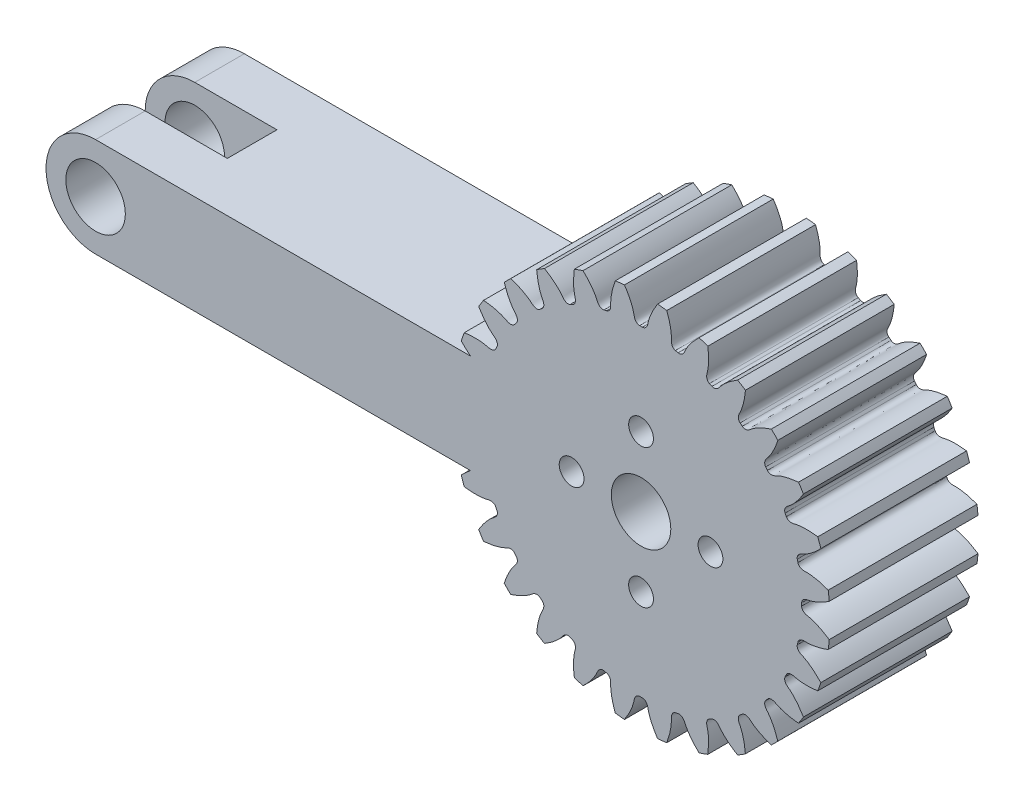
SolidWorks part; units mm, degrees
ref_plane "前视基准面" through (0, 0, 0) normal (0, 0, 1) x (1, 0, 0)
ref_plane "上视基准面" through (0, 0, 0) normal (0, 1, 0) x (1, 0, 0)
ref_plane "右视基准面" through (0, 0, 0) normal (1, 0, 0) x (0, 0, -1)
other "Configuration Table"
sketch "草图1" plane through (0, 0, 0) normal (0, 0, 1) x (1, 0, 0)
  line L4 (-55, -5) -> (-17.1897, -5)
  line L5 (-17.1897, 5) -> (-55, 5)
  circle A0 centre (0, 0) radius 3
  circle A1 centre (-55, 0) radius 3
  arc A104 (-18.1289, -5.8518) -> (-17.8223, -6.7281) centre (0, 0) ccw
  arc A105 (-14.6488, -6.9) -> (-14.528, -7.1508) centre (0, 0) ccw
  arc A106 (-16.3722, -9.7392) -> (-15.8784, -10.5252) centre (0, 0) ccw
  arc A107 (-12.7461, -9.9866) -> (-12.5725, -10.2043) centre (0, 0) ccw
  arc A108 (-13.7946, -13.1382) -> (-13.1382, -13.7946) centre (0, 0) ccw
  arc A109 (-10.2043, -12.5725) -> (-9.9866, -12.7461) centre (0, 0) ccw
  arc A110 (-10.5252, -15.8784) -> (-9.7392, -16.3722) centre (0, 0) ccw
  arc A111 (-7.1508, -14.528) -> (-6.9, -14.6488) centre (0, 0) ccw
  arc A112 (-6.7281, -17.8223) -> (-5.8518, -18.1289) centre (0, 0) ccw
  arc A113 (-3.7388, -15.755) -> (-3.4673, -15.8169) centre (0, 0) ccw
  arc A114 (-2.5935, -18.8726) -> (-1.6711, -18.9766) centre (0, 0) ccw
  arc A115 (-0.1392, -16.1919) -> (0.1392, -16.1919) centre (0, 0) ccw
  arc A116 (1.6711, -18.9766) -> (2.5935, -18.8726) centre (0, 0) ccw
  arc A117 (3.4673, -15.8169) -> (3.7388, -15.755) centre (0, 0) ccw
  arc A118 (5.8518, -18.1289) -> (6.7281, -17.8223) centre (0, 0) ccw
  arc A119 (6.9, -14.6488) -> (7.1508, -14.528) centre (0, 0) ccw
  arc A120 (9.7392, -16.3722) -> (10.5252, -15.8784) centre (0, 0) ccw
  arc A121 (9.9866, -12.7461) -> (10.2043, -12.5725) centre (0, 0) ccw
  arc A122 (13.1382, -13.7946) -> (13.7946, -13.1382) centre (0, 0) ccw
  arc A123 (12.5725, -10.2043) -> (12.7461, -9.9866) centre (0, 0) ccw
  arc A124 (15.8784, -10.5252) -> (16.3722, -9.7392) centre (0, 0) ccw
  arc A125 (14.528, -7.1508) -> (14.6488, -6.9) centre (0, 0) ccw
  arc A126 (17.8223, -6.7281) -> (18.1289, -5.8518) centre (0, 0) ccw
  arc A127 (15.755, -3.7388) -> (15.8169, -3.4673) centre (0, 0) ccw
  arc A128 (18.8726, -2.5935) -> (18.9766, -1.6711) centre (0, 0) ccw
  arc A129 (16.1919, -0.1392) -> (16.1919, 0.1392) centre (0, 0) ccw
  arc A130 (18.9766, 1.6711) -> (18.8726, 2.5935) centre (0, 0) ccw
  arc A131 (15.8169, 3.4673) -> (15.755, 3.7388) centre (0, 0) ccw
  arc A132 (18.1289, 5.8518) -> (17.8223, 6.7281) centre (0, 0) ccw
  arc A133 (14.6488, 6.9) -> (14.528, 7.1508) centre (0, 0) ccw
  arc A134 (16.3722, 9.7392) -> (15.8784, 10.5252) centre (0, 0) ccw
  arc A135 (12.7461, 9.9866) -> (12.5725, 10.2043) centre (0, 0) ccw
  arc A136 (13.7946, 13.1382) -> (13.1382, 13.7946) centre (0, 0) ccw
  arc A137 (10.2043, 12.5725) -> (9.9866, 12.7461) centre (0, 0) ccw
  arc A138 (10.5252, 15.8784) -> (9.7392, 16.3722) centre (0, 0) ccw
  arc A139 (7.1508, 14.528) -> (6.9, 14.6488) centre (0, 0) ccw
  arc A140 (6.7281, 17.8223) -> (5.8518, 18.1289) centre (0, 0) ccw
  arc A141 (3.7388, 15.755) -> (3.4673, 15.8169) centre (0, 0) ccw
  arc A142 (2.5935, 18.8726) -> (1.6711, 18.9766) centre (0, 0) ccw
  arc A143 (0.1392, 16.1919) -> (-0.1392, 16.1919) centre (0, 0) ccw
  arc A144 (-1.6711, 18.9766) -> (-2.5935, 18.8726) centre (0, 0) ccw
  arc A145 (-3.4673, 15.8169) -> (-3.7388, 15.755) centre (0, 0) ccw
  arc A146 (-5.8518, 18.1289) -> (-6.7281, 17.8223) centre (0, 0) ccw
  arc A147 (-6.9, 14.6488) -> (-7.1508, 14.528) centre (0, 0) ccw
  arc A148 (-9.7392, 16.3722) -> (-10.5252, 15.8784) centre (0, 0) ccw
  arc A149 (-9.9866, 12.7461) -> (-10.2043, 12.5725) centre (0, 0) ccw
  arc A150 (-13.1382, 13.7946) -> (-13.7946, 13.1382) centre (0, 0) ccw
  arc A151 (-12.5725, 10.2043) -> (-12.7461, 9.9866) centre (0, 0) ccw
  arc A152 (-15.8784, 10.5252) -> (-16.3722, 9.7392) centre (0, 0) ccw
  arc A153 (-14.528, 7.1508) -> (-14.6488, 6.9) centre (0, 0) ccw
  arc A154 (-17.8223, 6.7281) -> (-18.1289, 5.8518) centre (0, 0) ccw
  arc A155 (-55, 5) -> (-55, -5) centre (-55, 0) ccw
  spline S104 degree 3 poles (-17.1897, -5) (-17.2348, -5.0343) (-17.3497, -5.1242) (-17.5362, -5.2798) (-17.8086, -5.525) (-18.005, -5.7208) (-18.1289, -5.8518) knots 0.59534 0.59534 0.59534 0.59534 0.645252 0.723706 0.808982 0.967655 0.967655 0.967655 0.967655
  spline S105 degree 3 poles (-17.8223, -6.7281) (-17.6438, -6.7532) (-17.3681, -6.7839) (-17.0023, -6.8057) (-16.7348, -6.8117) (-16.4906, -6.808) (-16.2698, -6.7965) (-16.0729, -6.7788) (-15.8998, -6.7568) (-15.7506, -6.7322) (-15.6252, -6.7066) (-15.5335, -6.6846) (-15.4713, -6.6672) (-15.4305, -6.6561) (-15.3936, -6.6472) (-15.3338, -6.6343) (-15.2507, -6.6212) (-15.1426, -6.6153) (-15.0302, -6.6239) (-14.9083, -6.6553) (-14.7624, -6.7338) (-14.6816, -6.8327) (-14.6488, -6.9) knots 0.032345 0.032345 0.032345 0.032345 0.191018 0.276294 0.354748 0.42638 0.49119 0.549178 0.600343 0.644687 0.682208 0.712908 0.727669 0.739016 0.750139 0.761058 0.792861 0.824038 0.856152 0.891705 0.934026 1 1 1 1
  spline S106 degree 3 poles (-14.528, -7.1508) (-14.4959, -7.2184) (-14.4689, -7.3433) (-14.4985, -7.5063) (-14.5499, -7.6211) (-14.6133, -7.7144) (-14.6854, -7.7952) (-14.7474, -7.852) (-14.7948, -7.8908) (-14.8247, -7.9141) (-14.8589, -7.939) (-14.9112, -7.9768) (-14.9856, -8.0348) (-15.0838, -8.1169) (-15.1961, -8.2182) (-15.3212, -8.3398) (-15.4578, -8.4827) (-15.6044, -8.6481) (-15.7595, -8.8368) (-15.9217, -9.0496) (-16.1327, -9.3492) (-16.2806, -9.5839) (-16.3722, -9.7392) knots 0 0 0 0 0.065974 0.108295 0.143848 0.175962 0.207139 0.238942 0.249861 0.260984 0.272331 0.287092 0.317792 0.355313 0.399657 0.450822 0.50881 0.57362 0.645252 0.723706 0.808982 0.967655 0.967655 0.967655 0.967655
  spline S107 degree 3 poles (-15.8784, -10.5252) (-15.6987, -10.51) (-15.4231, -10.4786) (-15.0616, -10.4184) (-14.7995, -10.3647) (-14.5622, -10.3068) (-14.3496, -10.2465) (-14.1615, -10.1854) (-13.9976, -10.1255) (-13.8577, -10.0683) (-13.7411, -10.0154) (-13.6566, -9.9735) (-13.5998, -9.9428) (-13.5625, -9.9228) (-13.5285, -9.9059) (-13.4731, -9.8801) (-13.395, -9.8488) (-13.2909, -9.819) (-13.1794, -9.8023) (-13.0536, -9.8058) (-12.8939, -9.8499) (-12.7931, -9.9284) (-12.7461, -9.9866) knots 0.032345 0.032345 0.032345 0.032345 0.191018 0.276294 0.354748 0.42638 0.49119 0.549178 0.600343 0.644687 0.682208 0.712908 0.727669 0.739016 0.750139 0.761058 0.792861 0.824038 0.856152 0.891705 0.934026 1 1 1 1
  spline S108 degree 3 poles (-12.5725, -10.2043) (-12.5262, -10.2631) (-12.4721, -10.3788) (-12.4647, -10.5443) (-12.4893, -10.6677) (-12.5303, -10.7727) (-12.5826, -10.8676) (-12.6304, -10.9367) (-12.668, -10.9851) (-12.692, -11.0145) (-12.7197, -11.0464) (-12.7623, -11.0949) (-12.822, -11.168) (-12.8994, -11.2698) (-12.9864, -11.3936) (-13.0813, -11.5399) (-13.1826, -11.7097) (-13.2888, -11.9036) (-13.3981, -12.1221) (-13.5087, -12.3656) (-13.6478, -12.7047) (-13.7398, -12.9664) (-13.7946, -13.1382) knots 0 0 0 0 0.065974 0.108295 0.143848 0.175962 0.207139 0.238942 0.249861 0.260984 0.272331 0.287092 0.317792 0.355313 0.399657 0.450822 0.50881 0.57362 0.645252 0.723706 0.808982 0.967655 0.967655 0.967655 0.967655
  spline S109 degree 3 poles (-13.1382, -13.7946) (-12.9664, -13.7398) (-12.7047, -13.6478) (-12.3656, -13.5087) (-12.1221, -13.3981) (-11.9036, -13.2888) (-11.7097, -13.1826) (-11.5399, -13.0813) (-11.3936, -12.9864) (-11.2698, -12.8994) (-11.168, -12.822) (-11.0949, -12.7623) (-11.0464, -12.7197) (-11.0145, -12.692) (-10.9851, -12.668) (-10.9367, -12.6304) (-10.8676, -12.5826) (-10.7727, -12.5303) (-10.6677, -12.4893) (-10.5443, -12.4647) (-10.3788, -12.4721) (-10.2631, -12.5262) (-10.2043, -12.5725) knots 0.032345 0.032345 0.032345 0.032345 0.191018 0.276294 0.354748 0.42638 0.49119 0.549178 0.600343 0.644687 0.682208 0.712908 0.727669 0.739016 0.750139 0.761058 0.792861 0.824038 0.856152 0.891705 0.934026 1 1 1 1
  spline S110 degree 3 poles (-9.9866, -12.7461) (-9.9284, -12.7931) (-9.8499, -12.8939) (-9.8058, -13.0536) (-9.8023, -13.1794) (-9.819, -13.2909) (-9.8488, -13.395) (-9.8801, -13.4731) (-9.9059, -13.5285) (-9.9228, -13.5625) (-9.9428, -13.5998) (-9.9735, -13.6566) (-10.0154, -13.7411) (-10.0683, -13.8577) (-10.1255, -13.9976) (-10.1854, -14.1615) (-10.2465, -14.3496) (-10.3068, -14.5622) (-10.3647, -14.7995) (-10.4184, -15.0616) (-10.4786, -15.4231) (-10.51, -15.6987) (-10.5252, -15.8784) knots 0 0 0 0 0.065974 0.108295 0.143848 0.175962 0.207139 0.238942 0.249861 0.260984 0.272331 0.287092 0.317792 0.355313 0.399657 0.450822 0.50881 0.57362 0.645252 0.723706 0.808982 0.967655 0.967655 0.967655 0.967655
  spline S111 degree 3 poles (-9.7392, -16.3722) (-9.5839, -16.2806) (-9.3492, -16.1327) (-9.0496, -15.9217) (-8.8368, -15.7595) (-8.6481, -15.6044) (-8.4827, -15.4578) (-8.3398, -15.3212) (-8.2182, -15.1961) (-8.1169, -15.0838) (-8.0348, -14.9856) (-7.9768, -14.9112) (-7.939, -14.8589) (-7.9141, -14.8247) (-7.8908, -14.7948) (-7.852, -14.7474) (-7.7952, -14.6854) (-7.7144, -14.6133) (-7.6211, -14.5499) (-7.5063, -14.4985) (-7.3433, -14.4689) (-7.2184, -14.4959) (-7.1508, -14.528) knots 0.032345 0.032345 0.032345 0.032345 0.191018 0.276294 0.354748 0.42638 0.49119 0.549178 0.600343 0.644687 0.682208 0.712908 0.727669 0.739016 0.750139 0.761058 0.792861 0.824038 0.856152 0.891705 0.934026 1 1 1 1
  spline S112 degree 3 poles (-6.9, -14.6488) (-6.8327, -14.6816) (-6.7338, -14.7624) (-6.6553, -14.9083) (-6.6239, -15.0302) (-6.6153, -15.1426) (-6.6212, -15.2507) (-6.6343, -15.3338) (-6.6472, -15.3936) (-6.6561, -15.4305) (-6.6672, -15.4713) (-6.6846, -15.5335) (-6.7066, -15.6252) (-6.7322, -15.7506) (-6.7568, -15.8998) (-6.7788, -16.0729) (-6.7965, -16.2698) (-6.808, -16.4906) (-6.8117, -16.7348) (-6.8057, -17.0023) (-6.7839, -17.3681) (-6.7532, -17.6438) (-6.7281, -17.8223) knots 0 0 0 0 0.065974 0.108295 0.143848 0.175962 0.207139 0.238942 0.249861 0.260984 0.272331 0.287092 0.317792 0.355313 0.399657 0.450822 0.50881 0.57362 0.645252 0.723706 0.808982 0.967655 0.967655 0.967655 0.967655
  spline S113 degree 3 poles (-5.8518, -18.1289) (-5.7208, -18.005) (-5.525, -17.8086) (-5.2798, -17.5362) (-5.1084, -17.3308) (-4.959, -17.1376) (-4.8304, -16.9578) (-4.7214, -16.7928) (-4.6307, -16.6438) (-4.5569, -16.5118) (-4.4987, -16.3978) (-4.4588, -16.3124) (-4.4336, -16.2529) (-4.4168, -16.2141) (-4.4008, -16.1797) (-4.3735, -16.1249) (-4.332, -16.0518) (-4.2692, -15.9635) (-4.1924, -15.881) (-4.0919, -15.8053) (-3.9395, -15.7401) (-3.8118, -15.7387) (-3.7388, -15.755) knots 0.032345 0.032345 0.032345 0.032345 0.191018 0.276294 0.354748 0.42638 0.49119 0.549178 0.600343 0.644687 0.682208 0.712908 0.727669 0.739016 0.750139 0.761058 0.792861 0.824038 0.856152 0.891705 0.934026 1 1 1 1
  spline S114 degree 3 poles (-3.4673, -15.8169) (-3.3945, -15.8339) (-3.28, -15.8907) (-3.171, -16.0155) (-3.1133, -16.1273) (-3.0799, -16.235) (-3.0616, -16.3417) (-3.0559, -16.4256) (-3.0551, -16.4868) (-3.0556, -16.5248) (-3.0574, -16.567) (-3.0604, -16.6315) (-3.0615, -16.7259) (-3.0586, -16.8538) (-3.0494, -17.0047) (-3.0323, -17.1783) (-3.0057, -17.3743) (-2.9678, -17.592) (-2.917, -17.831) (-2.8517, -18.0904) (-2.749, -18.4422) (-2.6578, -18.7041) (-2.5935, -18.8726) knots 0 0 0 0 0.065974 0.108295 0.143848 0.175962 0.207139 0.238942 0.249861 0.260984 0.272331 0.287092 0.317792 0.355313 0.399657 0.450822 0.50881 0.57362 0.645252 0.723706 0.808982 0.967655 0.967655 0.967655 0.967655
  spline S115 degree 3 poles (-1.6711, -18.9766) (-1.5709, -18.8266) (-1.4237, -18.5915) (-1.2453, -18.2714) (-1.1239, -18.033) (-1.0212, -17.8114) (-0.9358, -17.6075) (-0.8662, -17.4224) (-0.811, -17.2569) (-0.7684, -17.1118) (-0.7371, -16.9878) (-0.7172, -16.8956) (-0.7058, -16.832) (-0.6981, -16.7904) (-0.6901, -16.7533) (-0.6758, -16.6938) (-0.6515, -16.6133) (-0.6099, -16.5133) (-0.5534, -16.4157) (-0.4723, -16.3196) (-0.3383, -16.2221) (-0.214, -16.1923) (-0.1392, -16.1919) knots 0.032345 0.032345 0.032345 0.032345 0.191018 0.276294 0.354748 0.42638 0.49119 0.549178 0.600343 0.644687 0.682208 0.712908 0.727669 0.739016 0.750139 0.761058 0.792861 0.824038 0.856152 0.891705 0.934026 1 1 1 1
  spline S116 degree 3 poles (0.1392, -16.1919) (0.214, -16.1923) (0.3383, -16.2221) (0.4723, -16.3196) (0.5534, -16.4157) (0.6099, -16.5133) (0.6515, -16.6133) (0.6758, -16.6938) (0.6901, -16.7533) (0.6981, -16.7904) (0.7058, -16.832) (0.7172, -16.8956) (0.7371, -16.9878) (0.7684, -17.1118) (0.811, -17.2569) (0.8662, -17.4224) (0.9358, -17.6075) (1.0212, -17.8114) (1.1239, -18.033) (1.2453, -18.2714) (1.4237, -18.5915) (1.5709, -18.8266) (1.6711, -18.9766) knots 0 0 0 0 0.065974 0.108295 0.143848 0.175962 0.207139 0.238942 0.249861 0.260984 0.272331 0.287092 0.317792 0.355313 0.399657 0.450822 0.50881 0.57362 0.645252 0.723706 0.808982 0.967655 0.967655 0.967655 0.967655
  spline S117 degree 3 poles (2.5935, -18.8726) (2.6578, -18.7041) (2.749, -18.4422) (2.8517, -18.0904) (2.917, -17.831) (2.9678, -17.592) (3.0057, -17.3743) (3.0323, -17.1783) (3.0494, -17.0047) (3.0586, -16.8538) (3.0615, -16.7259) (3.0604, -16.6315) (3.0574, -16.567) (3.0556, -16.5248) (3.0551, -16.4868) (3.0559, -16.4256) (3.0616, -16.3417) (3.0799, -16.235) (3.1133, -16.1273) (3.171, -16.0155) (3.28, -15.8907) (3.3945, -15.8339) (3.4673, -15.8169) knots 0.032345 0.032345 0.032345 0.032345 0.191018 0.276294 0.354748 0.42638 0.49119 0.549178 0.600343 0.644687 0.682208 0.712908 0.727669 0.739016 0.750139 0.761058 0.792861 0.824038 0.856152 0.891705 0.934026 1 1 1 1
  spline S118 degree 3 poles (3.7388, -15.755) (3.8118, -15.7387) (3.9395, -15.7401) (4.0919, -15.8053) (4.1924, -15.881) (4.2692, -15.9635) (4.332, -16.0518) (4.3735, -16.1249) (4.4008, -16.1797) (4.4168, -16.2141) (4.4336, -16.2529) (4.4588, -16.3124) (4.4987, -16.3978) (4.5569, -16.5118) (4.6307, -16.6438) (4.7214, -16.7928) (4.8304, -16.9578) (4.959, -17.1376) (5.1084, -17.3308) (5.2798, -17.5362) (5.525, -17.8086) (5.7208, -18.005) (5.8518, -18.1289) knots 0 0 0 0 0.065974 0.108295 0.143848 0.175962 0.207139 0.238942 0.249861 0.260984 0.272331 0.287092 0.317792 0.355313 0.399657 0.450822 0.50881 0.57362 0.645252 0.723706 0.808982 0.967655 0.967655 0.967655 0.967655
  spline S119 degree 3 poles (6.7281, -17.8223) (6.7532, -17.6438) (6.7839, -17.3681) (6.8057, -17.0023) (6.8117, -16.7348) (6.808, -16.4906) (6.7965, -16.2698) (6.7788, -16.0729) (6.7568, -15.8998) (6.7322, -15.7506) (6.7066, -15.6252) (6.6846, -15.5335) (6.6672, -15.4713) (6.6561, -15.4305) (6.6472, -15.3936) (6.6343, -15.3338) (6.6212, -15.2507) (6.6153, -15.1426) (6.6239, -15.0302) (6.6553, -14.9083) (6.7338, -14.7624) (6.8327, -14.6816) (6.9, -14.6488) knots 0.032345 0.032345 0.032345 0.032345 0.191018 0.276294 0.354748 0.42638 0.49119 0.549178 0.600343 0.644687 0.682208 0.712908 0.727669 0.739016 0.750139 0.761058 0.792861 0.824038 0.856152 0.891705 0.934026 1 1 1 1
  spline S120 degree 3 poles (7.1508, -14.528) (7.2184, -14.4959) (7.3433, -14.4689) (7.5063, -14.4985) (7.6211, -14.5499) (7.7144, -14.6133) (7.7952, -14.6854) (7.852, -14.7474) (7.8908, -14.7948) (7.9141, -14.8247) (7.939, -14.8589) (7.9768, -14.9112) (8.0348, -14.9856) (8.1169, -15.0838) (8.2182, -15.1961) (8.3398, -15.3212) (8.4827, -15.4578) (8.6481, -15.6044) (8.8368, -15.7595) (9.0496, -15.9217) (9.3492, -16.1327) (9.5839, -16.2806) (9.7392, -16.3722) knots 0 0 0 0 0.065974 0.108295 0.143848 0.175962 0.207139 0.238942 0.249861 0.260984 0.272331 0.287092 0.317792 0.355313 0.399657 0.450822 0.50881 0.57362 0.645252 0.723706 0.808982 0.967655 0.967655 0.967655 0.967655
  spline S121 degree 3 poles (10.5252, -15.8784) (10.51, -15.6987) (10.4786, -15.4231) (10.4184, -15.0616) (10.3647, -14.7995) (10.3068, -14.5622) (10.2465, -14.3496) (10.1854, -14.1615) (10.1255, -13.9976) (10.0683, -13.8577) (10.0154, -13.7411) (9.9735, -13.6566) (9.9428, -13.5998) (9.9228, -13.5625) (9.9059, -13.5285) (9.8801, -13.4731) (9.8488, -13.395) (9.819, -13.2909) (9.8023, -13.1794) (9.8058, -13.0536) (9.8499, -12.8939) (9.9284, -12.7931) (9.9866, -12.7461) knots 0.032345 0.032345 0.032345 0.032345 0.191018 0.276294 0.354748 0.42638 0.49119 0.549178 0.600343 0.644687 0.682208 0.712908 0.727669 0.739016 0.750139 0.761058 0.792861 0.824038 0.856152 0.891705 0.934026 1 1 1 1
  spline S122 degree 3 poles (10.2043, -12.5725) (10.2631, -12.5262) (10.3788, -12.4721) (10.5443, -12.4647) (10.6677, -12.4893) (10.7727, -12.5303) (10.8676, -12.5826) (10.9367, -12.6304) (10.9851, -12.668) (11.0145, -12.692) (11.0464, -12.7197) (11.0949, -12.7623) (11.168, -12.822) (11.2698, -12.8994) (11.3936, -12.9864) (11.5399, -13.0813) (11.7097, -13.1826) (11.9036, -13.2888) (12.1221, -13.3981) (12.3656, -13.5087) (12.7047, -13.6478) (12.9664, -13.7398) (13.1382, -13.7946) knots 0 0 0 0 0.065974 0.108295 0.143848 0.175962 0.207139 0.238942 0.249861 0.260984 0.272331 0.287092 0.317792 0.355313 0.399657 0.450822 0.50881 0.57362 0.645252 0.723706 0.808982 0.967655 0.967655 0.967655 0.967655
  spline S123 degree 3 poles (13.7946, -13.1382) (13.7398, -12.9664) (13.6478, -12.7047) (13.5087, -12.3656) (13.3981, -12.1221) (13.2888, -11.9036) (13.1826, -11.7097) (13.0813, -11.5399) (12.9864, -11.3936) (12.8994, -11.2698) (12.822, -11.168) (12.7623, -11.0949) (12.7197, -11.0464) (12.692, -11.0145) (12.668, -10.9851) (12.6304, -10.9367) (12.5826, -10.8676) (12.5303, -10.7727) (12.4893, -10.6677) (12.4647, -10.5443) (12.4721, -10.3788) (12.5262, -10.2631) (12.5725, -10.2043) knots 0.032345 0.032345 0.032345 0.032345 0.191018 0.276294 0.354748 0.42638 0.49119 0.549178 0.600343 0.644687 0.682208 0.712908 0.727669 0.739016 0.750139 0.761058 0.792861 0.824038 0.856152 0.891705 0.934026 1 1 1 1
  spline S124 degree 3 poles (12.7461, -9.9866) (12.7931, -9.9284) (12.8939, -9.8499) (13.0536, -9.8058) (13.1794, -9.8023) (13.2909, -9.819) (13.395, -9.8488) (13.4731, -9.8801) (13.5285, -9.9059) (13.5625, -9.9228) (13.5998, -9.9428) (13.6566, -9.9735) (13.7411, -10.0154) (13.8577, -10.0683) (13.9976, -10.1255) (14.1615, -10.1854) (14.3496, -10.2465) (14.5622, -10.3068) (14.7995, -10.3647) (15.0616, -10.4184) (15.4231, -10.4786) (15.6987, -10.51) (15.8784, -10.5252) knots 0 0 0 0 0.065974 0.108295 0.143848 0.175962 0.207139 0.238942 0.249861 0.260984 0.272331 0.287092 0.317792 0.355313 0.399657 0.450822 0.50881 0.57362 0.645252 0.723706 0.808982 0.967655 0.967655 0.967655 0.967655
  spline S125 degree 3 poles (16.3722, -9.7392) (16.2806, -9.5839) (16.1327, -9.3492) (15.9217, -9.0496) (15.7595, -8.8368) (15.6044, -8.6481) (15.4578, -8.4827) (15.3212, -8.3398) (15.1961, -8.2182) (15.0838, -8.1169) (14.9856, -8.0348) (14.9112, -7.9768) (14.8589, -7.939) (14.8247, -7.9141) (14.7948, -7.8908) (14.7474, -7.852) (14.6854, -7.7952) (14.6133, -7.7144) (14.5499, -7.6211) (14.4985, -7.5063) (14.4689, -7.3433) (14.4959, -7.2184) (14.528, -7.1508) knots 0.032345 0.032345 0.032345 0.032345 0.191018 0.276294 0.354748 0.42638 0.49119 0.549178 0.600343 0.644687 0.682208 0.712908 0.727669 0.739016 0.750139 0.761058 0.792861 0.824038 0.856152 0.891705 0.934026 1 1 1 1
  spline S126 degree 3 poles (14.6488, -6.9) (14.6816, -6.8327) (14.7624, -6.7338) (14.9083, -6.6553) (15.0302, -6.6239) (15.1426, -6.6153) (15.2507, -6.6212) (15.3338, -6.6343) (15.3936, -6.6472) (15.4305, -6.6561) (15.4713, -6.6672) (15.5335, -6.6846) (15.6252, -6.7066) (15.7506, -6.7322) (15.8998, -6.7568) (16.0729, -6.7788) (16.2698, -6.7965) (16.4906, -6.808) (16.7348, -6.8117) (17.0023, -6.8057) (17.3681, -6.7839) (17.6438, -6.7532) (17.8223, -6.7281) knots 0 0 0 0 0.065974 0.108295 0.143848 0.175962 0.207139 0.238942 0.249861 0.260984 0.272331 0.287092 0.317792 0.355313 0.399657 0.450822 0.50881 0.57362 0.645252 0.723706 0.808982 0.967655 0.967655 0.967655 0.967655
  spline S127 degree 3 poles (18.1289, -5.8518) (18.005, -5.7208) (17.8086, -5.525) (17.5362, -5.2798) (17.3308, -5.1084) (17.1376, -4.959) (16.9578, -4.8304) (16.7928, -4.7214) (16.6438, -4.6307) (16.5118, -4.5569) (16.3978, -4.4987) (16.3124, -4.4588) (16.2529, -4.4336) (16.2141, -4.4168) (16.1797, -4.4008) (16.1249, -4.3735) (16.0518, -4.332) (15.9635, -4.2692) (15.881, -4.1924) (15.8053, -4.0919) (15.7401, -3.9395) (15.7387, -3.8118) (15.755, -3.7388) knots 0.032345 0.032345 0.032345 0.032345 0.191018 0.276294 0.354748 0.42638 0.49119 0.549178 0.600343 0.644687 0.682208 0.712908 0.727669 0.739016 0.750139 0.761058 0.792861 0.824038 0.856152 0.891705 0.934026 1 1 1 1
  spline S128 degree 3 poles (15.8169, -3.4673) (15.8339, -3.3945) (15.8907, -3.28) (16.0155, -3.171) (16.1273, -3.1133) (16.235, -3.0799) (16.3417, -3.0616) (16.4256, -3.0559) (16.4868, -3.0551) (16.5248, -3.0556) (16.567, -3.0574) (16.6315, -3.0604) (16.7259, -3.0615) (16.8538, -3.0586) (17.0047, -3.0494) (17.1783, -3.0323) (17.3743, -3.0057) (17.592, -2.9678) (17.831, -2.917) (18.0904, -2.8517) (18.4422, -2.749) (18.7041, -2.6578) (18.8726, -2.5935) knots 0 0 0 0 0.065974 0.108295 0.143848 0.175962 0.207139 0.238942 0.249861 0.260984 0.272331 0.287092 0.317792 0.355313 0.399657 0.450822 0.50881 0.57362 0.645252 0.723706 0.808982 0.967655 0.967655 0.967655 0.967655
  spline S129 degree 3 poles (18.9766, -1.6711) (18.8266, -1.5709) (18.5915, -1.4237) (18.2714, -1.2453) (18.033, -1.1239) (17.8114, -1.0212) (17.6075, -0.9358) (17.4224, -0.8662) (17.2569, -0.811) (17.1118, -0.7684) (16.9878, -0.7371) (16.8956, -0.7172) (16.832, -0.7058) (16.7904, -0.6981) (16.7533, -0.6901) (16.6938, -0.6758) (16.6133, -0.6515) (16.5133, -0.6099) (16.4157, -0.5534) (16.3196, -0.4723) (16.2221, -0.3383) (16.1923, -0.214) (16.1919, -0.1392) knots 0.032345 0.032345 0.032345 0.032345 0.191018 0.276294 0.354748 0.42638 0.49119 0.549178 0.600343 0.644687 0.682208 0.712908 0.727669 0.739016 0.750139 0.761058 0.792861 0.824038 0.856152 0.891705 0.934026 1 1 1 1
  spline S130 degree 3 poles (16.1919, 0.1392) (16.1923, 0.214) (16.2221, 0.3383) (16.3196, 0.4723) (16.4157, 0.5534) (16.5133, 0.6099) (16.6133, 0.6515) (16.6938, 0.6758) (16.7533, 0.6901) (16.7904, 0.6981) (16.832, 0.7058) (16.8956, 0.7172) (16.9878, 0.7371) (17.1118, 0.7684) (17.2569, 0.811) (17.4224, 0.8662) (17.6075, 0.9358) (17.8114, 1.0212) (18.033, 1.1239) (18.2714, 1.2453) (18.5915, 1.4237) (18.8266, 1.5709) (18.9766, 1.6711) knots 0 0 0 0 0.065974 0.108295 0.143848 0.175962 0.207139 0.238942 0.249861 0.260984 0.272331 0.287092 0.317792 0.355313 0.399657 0.450822 0.50881 0.57362 0.645252 0.723706 0.808982 0.967655 0.967655 0.967655 0.967655
  spline S131 degree 3 poles (18.8726, 2.5935) (18.7041, 2.6578) (18.4422, 2.749) (18.0904, 2.8517) (17.831, 2.917) (17.592, 2.9678) (17.3743, 3.0057) (17.1783, 3.0323) (17.0047, 3.0494) (16.8538, 3.0586) (16.7259, 3.0615) (16.6315, 3.0604) (16.567, 3.0574) (16.5248, 3.0556) (16.4868, 3.0551) (16.4256, 3.0559) (16.3417, 3.0616) (16.235, 3.0799) (16.1273, 3.1133) (16.0155, 3.171) (15.8907, 3.28) (15.8339, 3.3945) (15.8169, 3.4673) knots 0.032345 0.032345 0.032345 0.032345 0.191018 0.276294 0.354748 0.42638 0.49119 0.549178 0.600343 0.644687 0.682208 0.712908 0.727669 0.739016 0.750139 0.761058 0.792861 0.824038 0.856152 0.891705 0.934026 1 1 1 1
  spline S132 degree 3 poles (15.755, 3.7388) (15.7387, 3.8118) (15.7401, 3.9395) (15.8053, 4.0919) (15.881, 4.1924) (15.9635, 4.2692) (16.0518, 4.332) (16.1249, 4.3735) (16.1797, 4.4008) (16.2141, 4.4168) (16.2529, 4.4336) (16.3124, 4.4588) (16.3978, 4.4987) (16.5118, 4.5569) (16.6438, 4.6307) (16.7928, 4.7214) (16.9578, 4.8304) (17.1376, 4.959) (17.3308, 5.1084) (17.5362, 5.2798) (17.8086, 5.525) (18.005, 5.7208) (18.1289, 5.8518) knots 0 0 0 0 0.065974 0.108295 0.143848 0.175962 0.207139 0.238942 0.249861 0.260984 0.272331 0.287092 0.317792 0.355313 0.399657 0.450822 0.50881 0.57362 0.645252 0.723706 0.808982 0.967655 0.967655 0.967655 0.967655
  spline S133 degree 3 poles (17.8223, 6.7281) (17.6438, 6.7532) (17.3681, 6.7839) (17.0023, 6.8057) (16.7348, 6.8117) (16.4906, 6.808) (16.2698, 6.7965) (16.0729, 6.7788) (15.8998, 6.7568) (15.7506, 6.7322) (15.6252, 6.7066) (15.5335, 6.6846) (15.4713, 6.6672) (15.4305, 6.6561) (15.3936, 6.6472) (15.3338, 6.6343) (15.2507, 6.6212) (15.1426, 6.6153) (15.0302, 6.6239) (14.9083, 6.6553) (14.7624, 6.7338) (14.6816, 6.8327) (14.6488, 6.9) knots 0.032345 0.032345 0.032345 0.032345 0.191018 0.276294 0.354748 0.42638 0.49119 0.549178 0.600343 0.644687 0.682208 0.712908 0.727669 0.739016 0.750139 0.761058 0.792861 0.824038 0.856152 0.891705 0.934026 1 1 1 1
  spline S134 degree 3 poles (14.528, 7.1508) (14.4959, 7.2184) (14.4689, 7.3433) (14.4985, 7.5063) (14.5499, 7.6211) (14.6133, 7.7144) (14.6854, 7.7952) (14.7474, 7.852) (14.7948, 7.8908) (14.8247, 7.9141) (14.8589, 7.939) (14.9112, 7.9768) (14.9856, 8.0348) (15.0838, 8.1169) (15.1961, 8.2182) (15.3212, 8.3398) (15.4578, 8.4827) (15.6044, 8.6481) (15.7595, 8.8368) (15.9217, 9.0496) (16.1327, 9.3492) (16.2806, 9.5839) (16.3722, 9.7392) knots 0 0 0 0 0.065974 0.108295 0.143848 0.175962 0.207139 0.238942 0.249861 0.260984 0.272331 0.287092 0.317792 0.355313 0.399657 0.450822 0.50881 0.57362 0.645252 0.723706 0.808982 0.967655 0.967655 0.967655 0.967655
  spline S135 degree 3 poles (15.8784, 10.5252) (15.6987, 10.51) (15.4231, 10.4786) (15.0616, 10.4184) (14.7995, 10.3647) (14.5622, 10.3068) (14.3496, 10.2465) (14.1615, 10.1854) (13.9976, 10.1255) (13.8577, 10.0683) (13.7411, 10.0154) (13.6566, 9.9735) (13.5998, 9.9428) (13.5625, 9.9228) (13.5285, 9.9059) (13.4731, 9.8801) (13.395, 9.8488) (13.2909, 9.819) (13.1794, 9.8023) (13.0536, 9.8058) (12.8939, 9.8499) (12.7931, 9.9284) (12.7461, 9.9866) knots 0.032345 0.032345 0.032345 0.032345 0.191018 0.276294 0.354748 0.42638 0.49119 0.549178 0.600343 0.644687 0.682208 0.712908 0.727669 0.739016 0.750139 0.761058 0.792861 0.824038 0.856152 0.891705 0.934026 1 1 1 1
  spline S136 degree 3 poles (12.5725, 10.2043) (12.5262, 10.2631) (12.4721, 10.3788) (12.4647, 10.5443) (12.4893, 10.6677) (12.5303, 10.7727) (12.5826, 10.8676) (12.6304, 10.9367) (12.668, 10.9851) (12.692, 11.0145) (12.7197, 11.0464) (12.7623, 11.0949) (12.822, 11.168) (12.8994, 11.2698) (12.9864, 11.3936) (13.0813, 11.5399) (13.1826, 11.7097) (13.2888, 11.9036) (13.3981, 12.1221) (13.5087, 12.3656) (13.6478, 12.7047) (13.7398, 12.9664) (13.7946, 13.1382) knots 0 0 0 0 0.065974 0.108295 0.143848 0.175962 0.207139 0.238942 0.249861 0.260984 0.272331 0.287092 0.317792 0.355313 0.399657 0.450822 0.50881 0.57362 0.645252 0.723706 0.808982 0.967655 0.967655 0.967655 0.967655
  spline S137 degree 3 poles (13.1382, 13.7946) (12.9664, 13.7398) (12.7047, 13.6478) (12.3656, 13.5087) (12.1221, 13.3981) (11.9036, 13.2888) (11.7097, 13.1826) (11.5399, 13.0813) (11.3936, 12.9864) (11.2698, 12.8994) (11.168, 12.822) (11.0949, 12.7623) (11.0464, 12.7197) (11.0145, 12.692) (10.9851, 12.668) (10.9367, 12.6304) (10.8676, 12.5826) (10.7727, 12.5303) (10.6677, 12.4893) (10.5443, 12.4647) (10.3788, 12.4721) (10.2631, 12.5262) (10.2043, 12.5725) knots 0.032345 0.032345 0.032345 0.032345 0.191018 0.276294 0.354748 0.42638 0.49119 0.549178 0.600343 0.644687 0.682208 0.712908 0.727669 0.739016 0.750139 0.761058 0.792861 0.824038 0.856152 0.891705 0.934026 1 1 1 1
  spline S138 degree 3 poles (9.9866, 12.7461) (9.9284, 12.7931) (9.8499, 12.8939) (9.8058, 13.0536) (9.8023, 13.1794) (9.819, 13.2909) (9.8488, 13.395) (9.8801, 13.4731) (9.9059, 13.5285) (9.9228, 13.5625) (9.9428, 13.5998) (9.9735, 13.6566) (10.0154, 13.7411) (10.0683, 13.8577) (10.1255, 13.9976) (10.1854, 14.1615) (10.2465, 14.3496) (10.3068, 14.5622) (10.3647, 14.7995) (10.4184, 15.0616) (10.4786, 15.4231) (10.51, 15.6987) (10.5252, 15.8784) knots 0 0 0 0 0.065974 0.108295 0.143848 0.175962 0.207139 0.238942 0.249861 0.260984 0.272331 0.287092 0.317792 0.355313 0.399657 0.450822 0.50881 0.57362 0.645252 0.723706 0.808982 0.967655 0.967655 0.967655 0.967655
  spline S139 degree 3 poles (9.7392, 16.3722) (9.5839, 16.2806) (9.3492, 16.1327) (9.0496, 15.9217) (8.8368, 15.7595) (8.6481, 15.6044) (8.4827, 15.4578) (8.3398, 15.3212) (8.2182, 15.1961) (8.1169, 15.0838) (8.0348, 14.9856) (7.9768, 14.9112) (7.939, 14.8589) (7.9141, 14.8247) (7.8908, 14.7948) (7.852, 14.7474) (7.7952, 14.6854) (7.7144, 14.6133) (7.6211, 14.5499) (7.5063, 14.4985) (7.3433, 14.4689) (7.2184, 14.4959) (7.1508, 14.528) knots 0.032345 0.032345 0.032345 0.032345 0.191018 0.276294 0.354748 0.42638 0.49119 0.549178 0.600343 0.644687 0.682208 0.712908 0.727669 0.739016 0.750139 0.761058 0.792861 0.824038 0.856152 0.891705 0.934026 1 1 1 1
  spline S140 degree 3 poles (6.9, 14.6488) (6.8327, 14.6816) (6.7338, 14.7624) (6.6553, 14.9083) (6.6239, 15.0302) (6.6153, 15.1426) (6.6212, 15.2507) (6.6343, 15.3338) (6.6472, 15.3936) (6.6561, 15.4305) (6.6672, 15.4713) (6.6846, 15.5335) (6.7066, 15.6252) (6.7322, 15.7506) (6.7568, 15.8998) (6.7788, 16.0729) (6.7965, 16.2698) (6.808, 16.4906) (6.8117, 16.7348) (6.8057, 17.0023) (6.7839, 17.3681) (6.7532, 17.6438) (6.7281, 17.8223) knots 0 0 0 0 0.065974 0.108295 0.143848 0.175962 0.207139 0.238942 0.249861 0.260984 0.272331 0.287092 0.317792 0.355313 0.399657 0.450822 0.50881 0.57362 0.645252 0.723706 0.808982 0.967655 0.967655 0.967655 0.967655
  spline S141 degree 3 poles (5.8518, 18.1289) (5.7208, 18.005) (5.525, 17.8086) (5.2798, 17.5362) (5.1084, 17.3308) (4.959, 17.1376) (4.8304, 16.9578) (4.7214, 16.7928) (4.6307, 16.6438) (4.5569, 16.5118) (4.4987, 16.3978) (4.4588, 16.3124) (4.4336, 16.2529) (4.4168, 16.2141) (4.4008, 16.1797) (4.3735, 16.1249) (4.332, 16.0518) (4.2692, 15.9635) (4.1924, 15.881) (4.0919, 15.8053) (3.9395, 15.7401) (3.8118, 15.7387) (3.7388, 15.755) knots 0.032345 0.032345 0.032345 0.032345 0.191018 0.276294 0.354748 0.42638 0.49119 0.549178 0.600343 0.644687 0.682208 0.712908 0.727669 0.739016 0.750139 0.761058 0.792861 0.824038 0.856152 0.891705 0.934026 1 1 1 1
  spline S142 degree 3 poles (3.4673, 15.8169) (3.3945, 15.8339) (3.28, 15.8907) (3.171, 16.0155) (3.1133, 16.1273) (3.0799, 16.235) (3.0616, 16.3417) (3.0559, 16.4256) (3.0551, 16.4868) (3.0556, 16.5248) (3.0574, 16.567) (3.0604, 16.6315) (3.0615, 16.7259) (3.0586, 16.8538) (3.0494, 17.0047) (3.0323, 17.1783) (3.0057, 17.3743) (2.9678, 17.592) (2.917, 17.831) (2.8517, 18.0904) (2.749, 18.4422) (2.6578, 18.7041) (2.5935, 18.8726) knots 0 0 0 0 0.065974 0.108295 0.143848 0.175962 0.207139 0.238942 0.249861 0.260984 0.272331 0.287092 0.317792 0.355313 0.399657 0.450822 0.50881 0.57362 0.645252 0.723706 0.808982 0.967655 0.967655 0.967655 0.967655
  spline S143 degree 3 poles (1.6711, 18.9766) (1.5709, 18.8266) (1.4237, 18.5915) (1.2453, 18.2714) (1.1239, 18.033) (1.0212, 17.8114) (0.9358, 17.6075) (0.8662, 17.4224) (0.811, 17.2569) (0.7684, 17.1118) (0.7371, 16.9878) (0.7172, 16.8956) (0.7058, 16.832) (0.6981, 16.7904) (0.6901, 16.7533) (0.6758, 16.6938) (0.6515, 16.6133) (0.6099, 16.5133) (0.5534, 16.4157) (0.4723, 16.3196) (0.3383, 16.2221) (0.214, 16.1923) (0.1392, 16.1919) knots 0.032345 0.032345 0.032345 0.032345 0.191018 0.276294 0.354748 0.42638 0.49119 0.549178 0.600343 0.644687 0.682208 0.712908 0.727669 0.739016 0.750139 0.761058 0.792861 0.824038 0.856152 0.891705 0.934026 1 1 1 1
  spline S144 degree 3 poles (-0.1392, 16.1919) (-0.214, 16.1923) (-0.3383, 16.2221) (-0.4723, 16.3196) (-0.5534, 16.4157) (-0.6099, 16.5133) (-0.6515, 16.6133) (-0.6758, 16.6938) (-0.6901, 16.7533) (-0.6981, 16.7904) (-0.7058, 16.832) (-0.7172, 16.8956) (-0.7371, 16.9878) (-0.7684, 17.1118) (-0.811, 17.2569) (-0.8662, 17.4224) (-0.9358, 17.6075) (-1.0212, 17.8114) (-1.1239, 18.033) (-1.2453, 18.2714) (-1.4237, 18.5915) (-1.5709, 18.8266) (-1.6711, 18.9766) knots 0 0 0 0 0.065974 0.108295 0.143848 0.175962 0.207139 0.238942 0.249861 0.260984 0.272331 0.287092 0.317792 0.355313 0.399657 0.450822 0.50881 0.57362 0.645252 0.723706 0.808982 0.967655 0.967655 0.967655 0.967655
  spline S145 degree 3 poles (-2.5935, 18.8726) (-2.6578, 18.7041) (-2.749, 18.4422) (-2.8517, 18.0904) (-2.917, 17.831) (-2.9678, 17.592) (-3.0057, 17.3743) (-3.0323, 17.1783) (-3.0494, 17.0047) (-3.0586, 16.8538) (-3.0615, 16.7259) (-3.0604, 16.6315) (-3.0574, 16.567) (-3.0556, 16.5248) (-3.0551, 16.4868) (-3.0559, 16.4256) (-3.0616, 16.3417) (-3.0799, 16.235) (-3.1133, 16.1273) (-3.171, 16.0155) (-3.28, 15.8907) (-3.3945, 15.8339) (-3.4673, 15.8169) knots 0.032345 0.032345 0.032345 0.032345 0.191018 0.276294 0.354748 0.42638 0.49119 0.549178 0.600343 0.644687 0.682208 0.712908 0.727669 0.739016 0.750139 0.761058 0.792861 0.824038 0.856152 0.891705 0.934026 1 1 1 1
  spline S146 degree 3 poles (-3.7388, 15.755) (-3.8118, 15.7387) (-3.9395, 15.7401) (-4.0919, 15.8053) (-4.1924, 15.881) (-4.2692, 15.9635) (-4.332, 16.0518) (-4.3735, 16.1249) (-4.4008, 16.1797) (-4.4168, 16.2141) (-4.4336, 16.2529) (-4.4588, 16.3124) (-4.4987, 16.3978) (-4.5569, 16.5118) (-4.6307, 16.6438) (-4.7214, 16.7928) (-4.8304, 16.9578) (-4.959, 17.1376) (-5.1084, 17.3308) (-5.2798, 17.5362) (-5.525, 17.8086) (-5.7208, 18.005) (-5.8518, 18.1289) knots 0 0 0 0 0.065974 0.108295 0.143848 0.175962 0.207139 0.238942 0.249861 0.260984 0.272331 0.287092 0.317792 0.355313 0.399657 0.450822 0.50881 0.57362 0.645252 0.723706 0.808982 0.967655 0.967655 0.967655 0.967655
  spline S147 degree 3 poles (-6.7281, 17.8223) (-6.7532, 17.6438) (-6.7839, 17.3681) (-6.8057, 17.0023) (-6.8117, 16.7348) (-6.808, 16.4906) (-6.7965, 16.2698) (-6.7788, 16.0729) (-6.7568, 15.8998) (-6.7322, 15.7506) (-6.7066, 15.6252) (-6.6846, 15.5335) (-6.6672, 15.4713) (-6.6561, 15.4305) (-6.6472, 15.3936) (-6.6343, 15.3338) (-6.6212, 15.2507) (-6.6153, 15.1426) (-6.6239, 15.0302) (-6.6553, 14.9083) (-6.7338, 14.7624) (-6.8327, 14.6816) (-6.9, 14.6488) knots 0.032345 0.032345 0.032345 0.032345 0.191018 0.276294 0.354748 0.42638 0.49119 0.549178 0.600343 0.644687 0.682208 0.712908 0.727669 0.739016 0.750139 0.761058 0.792861 0.824038 0.856152 0.891705 0.934026 1 1 1 1
  spline S148 degree 3 poles (-7.1508, 14.528) (-7.2184, 14.4959) (-7.3433, 14.4689) (-7.5063, 14.4985) (-7.6211, 14.5499) (-7.7144, 14.6133) (-7.7952, 14.6854) (-7.852, 14.7474) (-7.8908, 14.7948) (-7.9141, 14.8247) (-7.939, 14.8589) (-7.9768, 14.9112) (-8.0348, 14.9856) (-8.1169, 15.0838) (-8.2182, 15.1961) (-8.3398, 15.3212) (-8.4827, 15.4578) (-8.6481, 15.6044) (-8.8368, 15.7595) (-9.0496, 15.9217) (-9.3492, 16.1327) (-9.5839, 16.2806) (-9.7392, 16.3722) knots 0 0 0 0 0.065974 0.108295 0.143848 0.175962 0.207139 0.238942 0.249861 0.260984 0.272331 0.287092 0.317792 0.355313 0.399657 0.450822 0.50881 0.57362 0.645252 0.723706 0.808982 0.967655 0.967655 0.967655 0.967655
  spline S149 degree 3 poles (-10.5252, 15.8784) (-10.51, 15.6987) (-10.4786, 15.4231) (-10.4184, 15.0616) (-10.3647, 14.7995) (-10.3068, 14.5622) (-10.2465, 14.3496) (-10.1854, 14.1615) (-10.1255, 13.9976) (-10.0683, 13.8577) (-10.0154, 13.7411) (-9.9735, 13.6566) (-9.9428, 13.5998) (-9.9228, 13.5625) (-9.9059, 13.5285) (-9.8801, 13.4731) (-9.8488, 13.395) (-9.819, 13.2909) (-9.8023, 13.1794) (-9.8058, 13.0536) (-9.8499, 12.8939) (-9.9284, 12.7931) (-9.9866, 12.7461) knots 0.032345 0.032345 0.032345 0.032345 0.191018 0.276294 0.354748 0.42638 0.49119 0.549178 0.600343 0.644687 0.682208 0.712908 0.727669 0.739016 0.750139 0.761058 0.792861 0.824038 0.856152 0.891705 0.934026 1 1 1 1
  spline S150 degree 3 poles (-10.2043, 12.5725) (-10.2631, 12.5262) (-10.3788, 12.4721) (-10.5443, 12.4647) (-10.6677, 12.4893) (-10.7727, 12.5303) (-10.8676, 12.5826) (-10.9367, 12.6304) (-10.9851, 12.668) (-11.0145, 12.692) (-11.0464, 12.7197) (-11.0949, 12.7623) (-11.168, 12.822) (-11.2698, 12.8994) (-11.3936, 12.9864) (-11.5399, 13.0813) (-11.7097, 13.1826) (-11.9036, 13.2888) (-12.1221, 13.3981) (-12.3656, 13.5087) (-12.7047, 13.6478) (-12.9664, 13.7398) (-13.1382, 13.7946) knots 0 0 0 0 0.065974 0.108295 0.143848 0.175962 0.207139 0.238942 0.249861 0.260984 0.272331 0.287092 0.317792 0.355313 0.399657 0.450822 0.50881 0.57362 0.645252 0.723706 0.808982 0.967655 0.967655 0.967655 0.967655
  spline S151 degree 3 poles (-13.7946, 13.1382) (-13.7398, 12.9664) (-13.6478, 12.7047) (-13.5087, 12.3656) (-13.3981, 12.1221) (-13.2888, 11.9036) (-13.1826, 11.7097) (-13.0813, 11.5399) (-12.9864, 11.3936) (-12.8994, 11.2698) (-12.822, 11.168) (-12.7623, 11.0949) (-12.7197, 11.0464) (-12.692, 11.0145) (-12.668, 10.9851) (-12.6304, 10.9367) (-12.5826, 10.8676) (-12.5303, 10.7727) (-12.4893, 10.6677) (-12.4647, 10.5443) (-12.4721, 10.3788) (-12.5262, 10.2631) (-12.5725, 10.2043) knots 0.032345 0.032345 0.032345 0.032345 0.191018 0.276294 0.354748 0.42638 0.49119 0.549178 0.600343 0.644687 0.682208 0.712908 0.727669 0.739016 0.750139 0.761058 0.792861 0.824038 0.856152 0.891705 0.934026 1 1 1 1
  spline S152 degree 3 poles (-12.7461, 9.9866) (-12.7931, 9.9284) (-12.8939, 9.8499) (-13.0536, 9.8058) (-13.1794, 9.8023) (-13.2909, 9.819) (-13.395, 9.8488) (-13.4731, 9.8801) (-13.5285, 9.9059) (-13.5625, 9.9228) (-13.5998, 9.9428) (-13.6566, 9.9735) (-13.7411, 10.0154) (-13.8577, 10.0683) (-13.9976, 10.1255) (-14.1615, 10.1854) (-14.3496, 10.2465) (-14.5622, 10.3068) (-14.7995, 10.3647) (-15.0616, 10.4184) (-15.4231, 10.4786) (-15.6987, 10.51) (-15.8784, 10.5252) knots 0 0 0 0 0.065974 0.108295 0.143848 0.175962 0.207139 0.238942 0.249861 0.260984 0.272331 0.287092 0.317792 0.355313 0.399657 0.450822 0.50881 0.57362 0.645252 0.723706 0.808982 0.967655 0.967655 0.967655 0.967655
  spline S153 degree 3 poles (-16.3722, 9.7392) (-16.2806, 9.5839) (-16.1327, 9.3492) (-15.9217, 9.0496) (-15.7595, 8.8368) (-15.6044, 8.6481) (-15.4578, 8.4827) (-15.3212, 8.3398) (-15.1961, 8.2182) (-15.0838, 8.1169) (-14.9856, 8.0348) (-14.9112, 7.9768) (-14.8589, 7.939) (-14.8247, 7.9141) (-14.7948, 7.8908) (-14.7474, 7.852) (-14.6854, 7.7952) (-14.6133, 7.7144) (-14.5499, 7.6211) (-14.4985, 7.5063) (-14.4689, 7.3433) (-14.4959, 7.2184) (-14.528, 7.1508) knots 0.032345 0.032345 0.032345 0.032345 0.191018 0.276294 0.354748 0.42638 0.49119 0.549178 0.600343 0.644687 0.682208 0.712908 0.727669 0.739016 0.750139 0.761058 0.792861 0.824038 0.856152 0.891705 0.934026 1 1 1 1
  spline S154 degree 3 poles (-14.6488, 6.9) (-14.6816, 6.8327) (-14.7624, 6.7338) (-14.9083, 6.6553) (-15.0302, 6.6239) (-15.1426, 6.6153) (-15.2507, 6.6212) (-15.3338, 6.6343) (-15.3936, 6.6472) (-15.4305, 6.6561) (-15.4713, 6.6672) (-15.5335, 6.6846) (-15.6252, 6.7066) (-15.7506, 6.7322) (-15.8998, 6.7568) (-16.0729, 6.7788) (-16.2698, 6.7965) (-16.4906, 6.808) (-16.7348, 6.8117) (-17.0023, 6.8057) (-17.3681, 6.7839) (-17.6438, 6.7532) (-17.8223, 6.7281) knots 0 0 0 0 0.065974 0.108295 0.143848 0.175962 0.207139 0.238942 0.249861 0.260984 0.272331 0.287092 0.317792 0.355313 0.399657 0.450822 0.50881 0.57362 0.645252 0.723706 0.808982 0.967655 0.967655 0.967655 0.967655
  spline S155 degree 3 poles (-18.1289, 5.8518) (-18.005, 5.7208) (-17.8086, 5.525) (-17.5362, 5.2798) (-17.3497, 5.1242) (-17.2348, 5.0343) (-17.1897, 5) knots 0.032345 0.032345 0.032345 0.032345 0.191018 0.276294 0.354748 0.40466 0.40466 0.40466 0.40466
  dimension "D1" = 6
  dimension "D2" = 6
extrude "凸台-拉伸1" add sketch "草图1" along normal blind 5 and the other way blind 10
sketch "草图2" plane through (0, 0, 0) normal (0, 0, 1) x (1, 0, 0)
  circle A7 centre (7, 0) radius 1.25
  circle A8 centre (0, -7) radius 1.25
  circle A9 centre (0, 0) radius 1.5
  circle A10 centre (-7, 0) radius 1.25
  circle A11 centre (0, 7) radius 1.25
extrude "切除-拉伸2" cut sketch "草图2" along normal through all both and the other way through all contours A11 | A10 | A8 | A7
sketch "草图3" plane through (0, -5, 0) normal (0, -1, 0) x (1, 0, 0)
  line L0 (-46.7146, -2.5) -> (-64.2651, -2.5) construction
  line L1 (-46.7146, 0) -> (-46.7146, -5)
  line L2 (-46.7146, -5) -> (-64.2651, -5)
  line L3 (-64.2651, -5) -> (-64.2651, 0)
  line L4 (-55, -10) -> (-55, 5) construction
  line L5 (-46.7146, 0) -> (-64.2651, 0)
  point P2 (-55, -2.5)
  dimension "D1" = 2.5
extrude "切除-拉伸3" cut sketch "草图3" against normal blind 10
